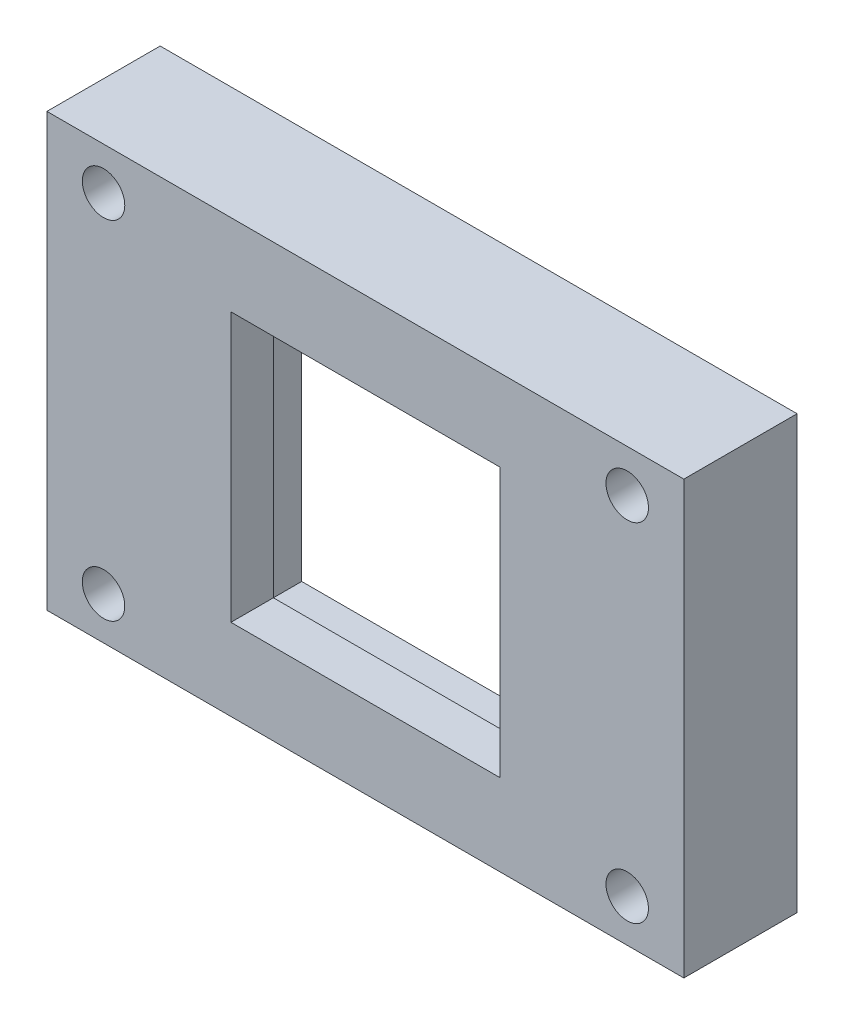
SolidWorks part; units mm, degrees
ref_plane "Front Plane" through (0, 0, 0) normal (0, 0, 1) x (1, 0, 0)
ref_plane "Top Plane" through (0, 0, 0) normal (0, 1, 0) x (1, 0, 0)
ref_plane "Right Plane" through (0, 0, 0) normal (1, 0, 0) x (0, 0, -1)
sketch "Sketch1" plane through (0, 0, 0) normal (0, 0, 1) x (1, 0, 0)
  line L0 (0, 0) -> (45, 0)
  line L1 (45, 0) -> (45, 30.5272)
  line L2 (45, 30.5272) -> (0, 30.5272)
  line L3 (0, 30.5272) -> (0, 0)
  line L4 (22.5, 30.5272) -> (22.5, 0) construction
  line L5 (0, 27.7636) -> (45, 27.7636) construction
  line L6 (0, 15.2636) -> (45, 15.2636) construction
  line L7 (0, 2.7636) -> (45, 2.7636) construction
  line L8 (10, 30.5272) -> (10, 0) construction
  line L9 (35, 30.5272) -> (35, 0) construction
  line L10 (10, 27.7636) -> (10, 2.7636)
  line L11 (10, 2.7636) -> (35, 2.7636)
  line L12 (35, 2.7636) -> (35, 27.7636)
  line L13 (35, 27.7636) -> (10, 27.7636)
  dimension "D1" = 45
  dimension "D2" = 30.5272
  dimension "D3" = 25
  dimension "D4" = 25
extrude "Boss-Extrude1" add sketch "Sketch1" along normal blind 10
sketch "Sketch2" plane through (10, 0, 0) normal (1, 0, 0) x (0, 0, -1)
  line L0 (-10, 27.7636) -> (0, 27.7636) construction
  line L1 (0, 27.7636) -> (0, 2.7636) construction
  line L2 (-10, 2.7636) -> (0, 2.7636) construction
  line L3 (-10, 27.7636) -> (-10, 2.7636) construction
  line L4 (-10, 27.7636) -> (0, 27.7636)
  line L5 (0, 27.7636) -> (0, 2.7636)
  line L6 (-10, 2.7636) -> (0, 2.7636)
  line L7 (-10, 27.7636) -> (-10, 2.7636)
  line L8 (-5, 27.7636) -> (-5, 2.7636)
  line M5 (-10, 27.7636) -> (-10, 2.7636)
  line M6 (-10, 2.7636) -> (0, 2.7636)
  dimension "D1" = 5
extrude "Boss-Extrude2" add sketch "Sketch2" along normal blind 3 contours L8 L4 M5 M6
sketch "Sketch3" plane through (35, 0, 0) normal (-1, 0, 0) x (0, 0, 1)
  line L0 (5, 27.7636) -> (10, 27.7636) construction
  line L1 (10, 27.7636) -> (10, 2.7636) construction
  line L2 (10, 2.7636) -> (5, 2.7636) construction
  line L3 (5, 27.7636) -> (5, 2.7636) construction
  line L4 (0, 27.7636) -> (0, 2.7636)
  line L5 (0, 2.7636) -> (10, 2.7636)
  line L6 (10, 2.7636) -> (10, 27.7636)
  line L7 (10, 27.7636) -> (0, 27.7636)
  line L8 (0, 27.7636) -> (0, 2.7636)
  line L9 (0, 2.7636) -> (10, 2.7636)
  line L10 (10, 2.7636) -> (10, 27.7636)
  line L11 (10, 27.7636) -> (0, 27.7636)
  line L12 (5, 27.7636) -> (10, 27.7636)
  line L13 (10, 27.7636) -> (10, 2.7636)
  line L14 (10, 2.7636) -> (5, 2.7636)
  line L15 (5, 27.7636) -> (5, 2.7636)
  line M7 (10, 2.7636) -> (10, 27.7636)
  line M8 (10, 27.7636) -> (0, 27.7636)
  dimension "D1" = 0
extrude "Boss-Extrude3" add sketch "Sketch3" along normal blind 3 contours L15 L9 M8 M7
sketch "Sketch4" plane through (0, 27.7636, 0) normal (0, -1, 0) x (1, 0, 0)
  line L0 (13, 5) -> (32, 5)
  line L8 (35, 0) -> (35, 5)
  line L9 (35, 5) -> (32, 5)
  line L10 (32, 5) -> (32, 10)
  line L11 (32, 10) -> (13, 10)
  line L12 (13, 10) -> (13, 5)
  line L13 (13, 5) -> (10, 5)
  line L14 (10, 5) -> (10, 0)
  line L15 (10, 0) -> (35, 0)
  line L16 (35, 0) -> (35, 5)
  line L17 (35, 5) -> (32, 5)
  line L18 (32, 5) -> (32, 10)
  line L19 (32, 10) -> (13, 10)
  line L20 (13, 10) -> (13, 5)
  line L21 (13, 5) -> (10, 5)
  line L22 (10, 5) -> (10, 0)
  line L23 (10, 0) -> (35, 0)
  line M11 (32, 5) -> (32, 10)
  line M12 (32, 10) -> (13, 10)
  line M13 (13, 10) -> (13, 5)
  dimension "D1" = 0
extrude "Boss-Extrude4" add sketch "Sketch4" along normal blind 3 contours L0 M13 M11 M12
sketch "Sketch5" plane through (0, 2.7636, 0) normal (0, 1, 0) x (1, 0, 0)
  line L0 (13, -10) -> (13, -5) construction
  line L1 (13, -5) -> (32, -5) construction
  line L2 (32, -5) -> (32, -10) construction
  line L3 (32, -10) -> (13, -10) construction
  line L4 (13, -10) -> (13, -5)
  line L5 (13, -5) -> (32, -5)
  line L6 (32, -5) -> (32, -10)
  line L7 (32, -10) -> (13, -10)
  line L8 (32, -10) -> (32, -5)
  line L9 (32, -5) -> (35, -5)
  line L10 (35, -5) -> (35, 0)
  line L11 (35, 0) -> (10, 0)
  line L12 (10, 0) -> (10, -5)
  line L13 (10, -5) -> (13, -5)
  line L14 (13, -5) -> (13, -10)
  line L15 (13, -10) -> (32, -10)
  line L16 (32, -10) -> (32, -5)
  line L17 (32, -5) -> (35, -5)
  line L18 (35, -5) -> (35, 0)
  line L19 (35, 0) -> (10, 0)
  line L20 (10, 0) -> (10, -5)
  line L21 (10, -5) -> (13, -5)
  line L22 (13, -5) -> (13, -10)
  line L23 (13, -10) -> (32, -10)
  line L24 (32, -5) -> (32, -10)
  line L25 (32, -10) -> (13, -10)
  line L26 (13, -5) -> (32, -5)
  line L27 (13, -10) -> (13, -5)
  line M9 (32, -10) -> (32, -5)
  line M15 (13, -5) -> (13, -10)
  line M16 (13, -10) -> (32, -10)
  dimension "D1" = 0
extrude "Boss-Extrude5" add sketch "Sketch5" along normal blind 3 contours L5 M15 M16 M9
sketch "Sketch6" plane through (0, 0, 10) normal (0, 0, 1) x (1, 0, 0)
  line L0 (0, 15.2636) -> (45, 15.2636) construction
  line L1 (0, 30.5272) -> (0, 0) construction
  line L2 (45, 0) -> (45, 30.5272) construction
  line L3 (22.5, 30.5272) -> (22.5, 0) construction
  line L4 (45, 30.5272) -> (0, 30.5272) construction
  line L5 (0, 0) -> (45, 0) construction
  line L6 (0, 3) -> (45, 3) construction
  line L7 (4, 30.5272) -> (4, 0) construction
  line L8 (41, 30.5272) -> (41, 0) construction
  line L9 (0, 27.5272) -> (45, 27.5272) construction
  circle A0 centre (4, 27.5272) radius 1.5
  circle A2 centre (41, 27.5272) radius 1.5
  circle A3 centre (41, 3) radius 1.5
  circle A5 centre (4, 3) radius 1.5
  circle A6 centre (22.5, 27.5272) radius 1.5 [skipped]
  dimension "D3" = 3
  dimension "D1" = 3
  dimension "D2" = 4
  dimension "D4" = 3
extrude "Cut-Extrude1" cut sketch "Sketch6" against normal through all
sketch "Sketch7" plane through (45, 0, 0) normal (1, 0, 0) x (0, 0, -1)
  line L0 (-8, 0) -> (-8, 30.5272)
  line L1 (-10, 0) -> (0, 0) construction
  line L2 (-10, 30.5272) -> (0, 30.5272) construction
  line L3 (-10, 0) -> (-10, 30.5272) construction
  line M3 (0, 30.5272) -> (-10, 30.5272)
  line M4 (-10, 30.5272) -> (-10, 0)
  line M5 (-10, 0) -> (0, 0)
  dimension "D1" = 2
extrude "Cut-Extrude2" cut sketch "Sketch7" against normal through all and the other way through all contours L0 M5 M3 M4
